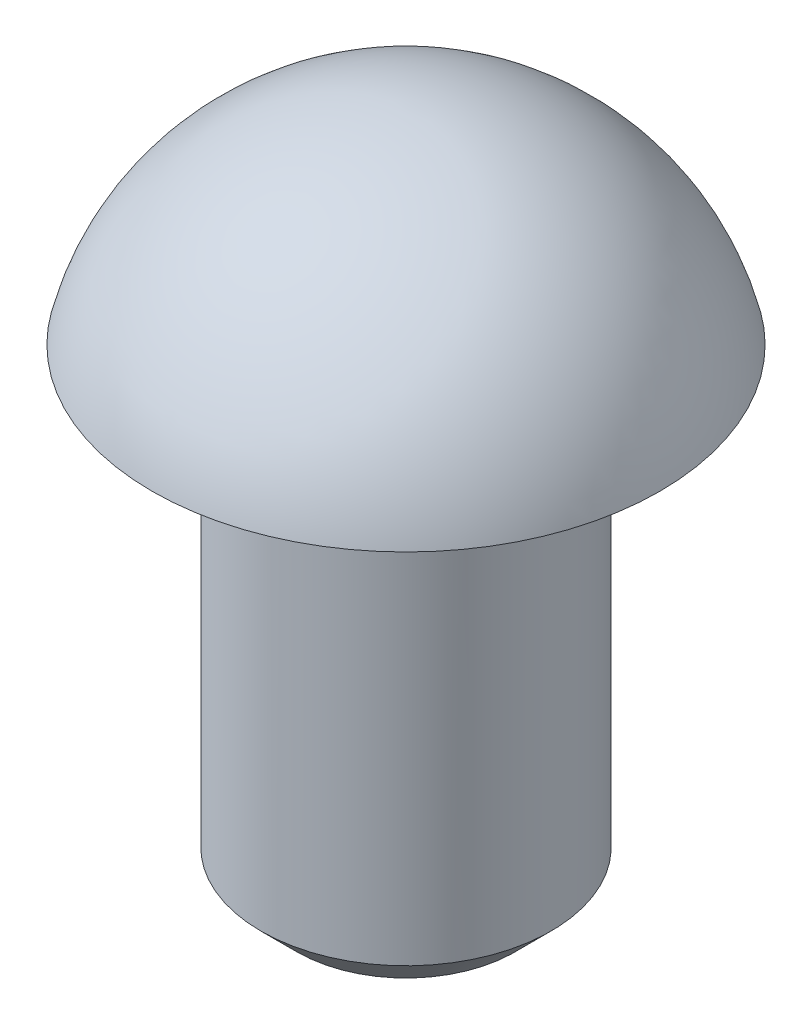
SolidWorks part; units mm, degrees
material "Cast Carbon Steel"
ref_plane "Front Plane" through (0, 0, 0) normal (0, 0, 1) x (1, 0, 0)
ref_plane "Top Plane" through (0, 0, 0) normal (0, 1, 0) x (1, 0, 0)
ref_plane "Right Plane" through (0, 0, 0) normal (1, 0, 0) x (0, 0, -1)
sketch "Sketch1" plane through (0, 0, 0) normal (0, 1, 0) x (1, 0, 0)
  circle A0 centre (0, 0) radius 2
  dimension "D1" = 4
extrude "Boss-Extrude1" add sketch "Sketch1" along normal mid plane 6.5
chamfer "Chamfer1" distance 0.5 angle 45 1 edges at (0, -3.25, 2)
sketch "Sketch2" plane through (0, 0, 0) normal (1, 0, 0) x (0, 0, -1)
  line L0 (0, 1.8508) -> (0, 6.0074) construction
  line L1 (0, 3.25) -> (-3.5, 3.25)
  line L3 (2, 3.25) -> (-2, 3.25) construction
  line L4 (0, 6.0074) -> (0, 3.25)
  arc A0 (-3.5, 3.25) -> (0, 6.0074) centre (0, 2.4074) cw
  dimension "D1" = 3.6
  dimension "D2" = 3.5
revolve "Revolve1" add sketch "Sketch2" angle 360 about L0
